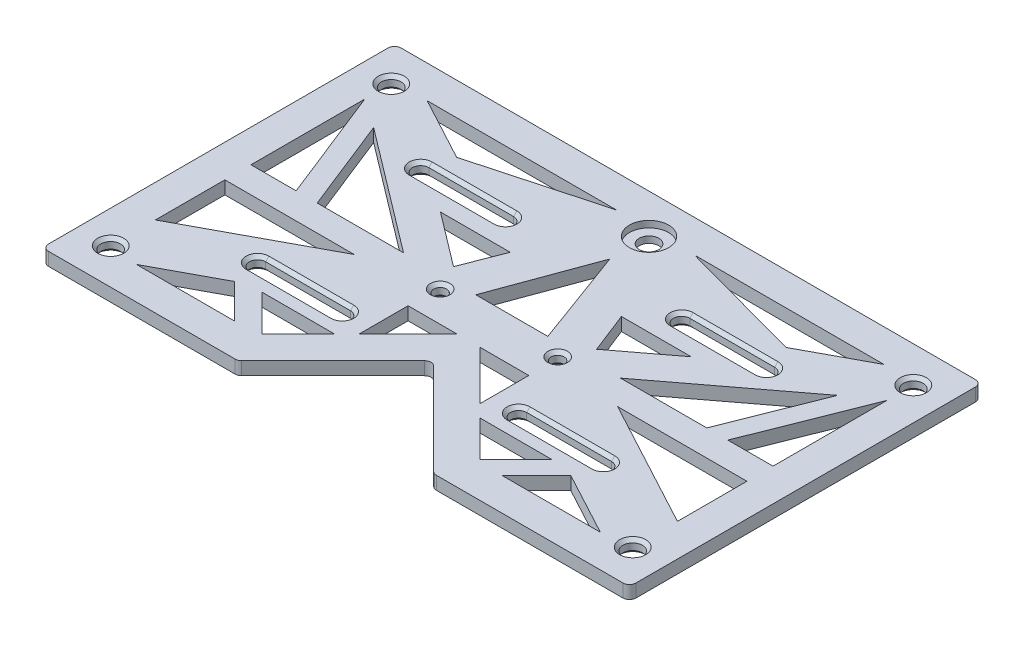
SolidWorks part; units mm, degrees
ref_plane "前视基准面" through (0, 0, 0) normal (0, 0, 1) x (1, 0, 0)
ref_plane "上视基准面" through (0, 0, 0) normal (0, 1, 0) x (1, 0, 0)
ref_plane "右视基准面" through (0, 0, 0) normal (1, 0, 0) x (0, 0, -1)
other "Configuration Table"
sketch "草图1" plane through (0, 0, 0) normal (0, 1, 0) x (1, 0, 0)
  line L0 (0, 26.8995) -> (0, -26.8995) construction
  line L1 (-45, 26.8995) -> (45, 26.8995)
  line L2 (-45, 26.8995) -> (-45, -27.1005)
  line L3 (-45, -27.1005) -> (-15, -27.1005)
  line L4 (45, 26.8995) -> (45, -27.1005)
  line L5 (45, -0.1005) -> (-45, -0.1005) construction
  line L6 (-26.5, 12.3995) -> (-13.5, 12.3995) construction
  line L7 (-26.5, 13.6495) -> (-13.5, 13.6495)
  line L8 (-26.5, 11.1495) -> (-13.5, 11.1495)
  line L9 (-26.5, -12.6005) -> (-13.5, -12.6005) construction
  line L10 (-26.5, -11.3505) -> (-13.5, -11.3505)
  line L11 (-26.5, -13.8505) -> (-13.5, -13.8505)
  line L12 (-40, -21.6005) -> (40, -21.6005) construction
  line L13 (-40, 21.3995) -> (-40, -21.6005) construction
  line L14 (-40, 21.3995) -> (40, 21.3995) construction
  line L15 (40, 21.3995) -> (40, -21.6005) construction
  line L16 (-38.5, 21.3995) -> (-38.5, -21.6005) construction
  line L17 (38.5, -21.6005) -> (38.5, 21.3995) construction
  line L18 (40, 19.8995) -> (-40, 19.8995) construction
  line L19 (-40, -20.1005) -> (40, -20.1005) construction
  line L20 (-20, 12.3995) -> (-20, -12.6005) construction
  line L21 (13.5, 12.3995) -> (26.5, 12.3995) construction
  line L22 (13.5, 13.6495) -> (26.5, 13.6495)
  line L23 (13.5, 11.1495) -> (26.5, 11.1495)
  line L24 (13.5, -12.6005) -> (26.5, -12.6005) construction
  line L25 (13.5, -11.3505) -> (26.5, -11.3505)
  line L26 (13.5, -13.8505) -> (26.5, -13.8505)
  line L27 (20, 12.3995) -> (20, -12.6005) construction
  line L31 (-15, -27.1005) -> (0, -12.1005)
  line L32 (0, -12.1005) -> (15, -27.1005)
  line L34 (0, -12.1005) -> (0, -26.8995) construction
  line L35 (15, -27.1005) -> (45, -27.1005)
  line L36 (-9, -2.1005) -> (9, -2.1005) construction
  arc A0 (-26.5, 13.6495) -> (-26.5, 11.1495) centre (-26.5, 12.3995) ccw
  arc A1 (-13.5, 11.1495) -> (-13.5, 13.6495) centre (-13.5, 12.3995) ccw
  arc A2 (-26.5, -11.3505) -> (-26.5, -13.8505) centre (-26.5, -12.6005) ccw
  arc A3 (-13.5, -13.8505) -> (-13.5, -11.3505) centre (-13.5, -12.6005) ccw
  circle A4 centre (-40, 21.3995) radius 1.5
  circle A5 centre (-40, -21.6005) radius 1.5
  circle A6 centre (40, 21.3995) radius 1.5
  circle A7 centre (40, -21.6005) radius 1.5
  arc A8 (13.5, 13.6495) -> (13.5, 11.1495) centre (13.5, 12.3995) ccw
  arc A9 (26.5, 11.1495) -> (26.5, 13.6495) centre (26.5, 12.3995) ccw
  arc A10 (13.5, -11.3505) -> (13.5, -13.8505) centre (13.5, -12.6005) ccw
  arc A11 (26.5, -13.8505) -> (26.5, -11.3505) centre (26.5, -12.6005) ccw
  circle A12 centre (-9, -2.1005) radius 1
  circle A13 centre (9, -2.1005) radius 1
  circle A14 centre (0, 20.8995) radius 1.5
  point P8 (0, 0)
  point P12 (-20, 12.3995)
  point P17 (-27.75, 12.3995)
  point P18 (-12.25, 12.3995)
  point P21 (-20, -12.6005)
  point P36 (0, -21.6005)
  point P37 (-40, -0.1005)
  point P48 (-20, -0.1005)
  point P51 (20, 12.3995)
  point P60 (20, -12.6005)
  point P65 (0, -2.1005)
  point P69 (20, -0.1005)
  dimension "D6" = 3
  dimension "D14" = 2
  dimension "D17" = 3
  dimension "D19" = 2
  dimension "D1" = 90
  dimension "D2" = 54
  dimension "D3" = 13
  dimension "D4" = 2.5
  dimension "D5" = 15.5
  dimension "D7" = 80
  dimension "D8" = 43
  dimension "D9" = 25
  dimension "D10" = 20
  dimension "D11" = 20
  dimension "D12" = 25
  dimension "D13" = 15
  dimension "D15" = 18
  dimension "D18" = 23
  dimension "D21" = 25
extrude "凸台-拉伸1" add sketch "草图1" along normal blind 2
sketch "草图3" plane through (0, 2, 0) normal (0, 1, 0) x (1, 0, 0)
  circle A2 centre (0, 20.8995) radius 3
  circle A3 centre (0, 20.8995) radius 3
  dimension "D1" = 1.5
extrude "切除-拉伸2" cut sketch "草图3" against normal blind 1 contours A3
sketch "草图2" plane through (0, 2, 0) normal (0, 1, 0) x (1, 0, 0)
  line L8 (-45, 26.8995) -> (-45, -27.1005) construction
  line L16 (45, 26.8995) -> (-45, 26.8995) construction
  line L17 (45, -27.1005) -> (45, 26.8995) construction
  line L18 (-45, -27.1005) -> (-15, -27.1005) construction
  line L19 (-35.5413, -22.1005) -> (-20.5238, -22.1005)
  line L33 (-20.5238, -22.1005) -> (-25.7738, -16.8505)
  line L40 (-25.7738, -16.8505) -> (-35.5413, -22.1005)
  line L47 (-16.6761, -21.7055) -> (-22.2208, -16.1608)
  line L53 (-22.2208, -16.1608) -> (-11.1314, -16.1608)
  line L60 (-11.1314, -16.1608) -> (-16.6761, -21.7055)
  line L61 (-45, -0.1005) -> (45, -0.1005) construction
  line L62 (-40, -14.7479) -> (-20.1909, -4.1005)
  line L63 (-20.1909, -4.1005) -> (-40, -4.1005)
  line L64 (-40, -4.1005) -> (-40, -14.7479)
  line L68 (0, 14.8995) -> (-5.5196, -0.129)
  line L69 (-5.5196, -0.129) -> (5.5196, -0.129)
  line L70 (5.5196, -0.129) -> (0, 14.8995)
  line L71 (0, 14.8995) -> (0, -0.129) construction
  line L72 (-26.5, -13.8505) -> (-13.5, -13.8505) construction
  line L73 (-15, -27.1005) -> (0, -12.1005) construction
  line L74 (-40, -21.6005) -> (40, 21.3995) construction
  line L75 (-40, 21.3995) -> (40, -21.6005) construction
  line L76 (-1.7459, -6.7753) -> (-9.25, -14.2794)
  line L77 (-9.25, -14.2794) -> (-9.25, -6.7753)
  line L78 (-9.25, -6.7753) -> (-1.7459, -6.7753)
  line L79 (-35, 21.8995) -> (-6, 21.8995)
  line L80 (-6, 21.8995) -> (-25.2326, 16.6495)
  line L81 (-25.2326, 16.6495) -> (-35, 21.8995)
  line L85 (-13.5, 13.6495) -> (-26.5, 13.6495) construction
  line L86 (0, 20.8995) -> (-9, -2.1005) construction
  line L87 (-45, -2.1005) -> (-9, -2.1005) construction
  line L88 (9, -2.1005) -> (0, 20.8995) construction
  line L89 (0, 20.8995) -> (0, -12.1005) construction
  line L96 (-29.8493, -0.1005) -> (-35.5436, 14.2406)
  line L97 (-35.5436, 14.2406) -> (-16.6256, -0.1005)
  line L98 (-16.6256, -0.1005) -> (-29.8493, -0.1005)
  line L99 (-40, 21.3995) -> (-26.5, -12.6005) construction
  line L100 (-13.5, -12.6005) -> (-9, -2.1005) construction
  line L101 (26.5, -12.6005) -> (40, 21.3995) construction
  line L102 (13.5, -12.6005) -> (9, -2.1005) construction
  line L103 (-9, -2.1005) -> (9, -2.1005) construction
  line L104 (9, -2.1005) -> (45, -2.1005) construction
  line L105 (-40, 17.3349) -> (-40, -0.1005)
  line L106 (-40, -0.1005) -> (-33.0772, -0.1005)
  line L107 (-33.0772, -0.1005) -> (-40, 17.3349)
  line L108 (-40, 21.3995) -> (-9, -2.1005) construction
  line L109 (9, -2.1005) -> (40, 21.3995) construction
  line L110 (-19.2106, 8.1495) -> (-8.5203, 8.1495)
  line L111 (-8.5203, 8.1495) -> (-10.9659, 1.8995)
  line L112 (-10.9659, 1.8995) -> (-19.2106, 8.1495)
  line L113 (-26.5, 11.1495) -> (-13.5, 11.1495) construction
  line L114 (0, 20.8995) -> (-13.5, 12.3995) construction
  line L115 (-26.5, 12.3995) -> (0, 20.8995) construction
  line L116 (9.25, -14.2794) -> (9.25, -6.7753)
  line L117 (1.7459, -6.7753) -> (9.25, -14.2794)
  line L118 (9.25, -6.7753) -> (1.7459, -6.7753)
  line L119 (22.2208, -16.1608) -> (11.1314, -16.1608)
  line L120 (16.6761, -21.7055) -> (22.2208, -16.1608)
  line L121 (11.1314, -16.1608) -> (16.6761, -21.7055)
  line L122 (20.5238, -22.1005) -> (25.7738, -16.8505)
  line L123 (35.5413, -22.1005) -> (20.5238, -22.1005)
  line L124 (25.7738, -16.8505) -> (35.5413, -22.1005)
  line L125 (20.1909, -4.1005) -> (40, -4.1005)
  line L126 (40, -14.7479) -> (20.1909, -4.1005)
  line L127 (40, -4.1005) -> (40, -14.7479)
  line L128 (8.5203, 8.1495) -> (10.9659, 1.8995)
  line L129 (19.2106, 8.1495) -> (8.5203, 8.1495)
  line L130 (10.9659, 1.8995) -> (19.2106, 8.1495)
  line L131 (35.5436, 14.2406) -> (16.6256, -0.1005)
  line L132 (29.8493, -0.1005) -> (35.5436, 14.2406)
  line L133 (16.6256, -0.1005) -> (29.8493, -0.1005)
  line L134 (40, -0.1005) -> (33.0772, -0.1005)
  line L135 (40, 17.3349) -> (40, -0.1005)
  line L136 (33.0772, -0.1005) -> (40, 17.3349)
  line L137 (6, 21.8995) -> (25.2326, 16.6495)
  line L138 (35, 21.8995) -> (6, 21.8995)
  line L139 (25.2326, 16.6495) -> (35, 21.8995)
  circle A0 centre (0, 20.8995) radius 3 construction
  circle A1 centre (9, -2.1005) radius 1 construction
  arc A3 (-26.5, -11.3505) -> (-26.5, -13.8505) centre (-26.5, -12.6005) ccw construction
  arc A4 (-13.5, -13.8505) -> (-13.5, -11.3505) centre (-13.5, -12.6005) ccw construction
  circle A5 centre (-40, 21.3995) radius 1.5 construction
  circle A6 centre (-9, -2.1005) radius 1 construction
  point P59 (-12.25, -12.6005)
  dimension "D4" = 4
  dimension "D12" = 4.5
  dimension "D1" = 6
  dimension "D3" = 5
  dimension "D5" = 6
  dimension "D6" = 2.3104
  dimension "D7" = 5
  dimension "D8" = 3
  dimension "D9" = 5
  dimension "D10" = 3
  dimension "D11" = 5
  dimension "D13" = 3
  dimension "D14" = 2
  dimension "D15" = 3
  dimension "D16" = 5
  dimension "D17" = 1.5
  dimension "D18" = 5
  dimension "D19" = 3
  dimension "D20" = 2
  dimension "D21" = 5
  dimension "D22" = 4
  dimension "D23" = 2
  dimension "D24" = 1.5
  dimension "D25" = 1.5
  dimension "D26" = 2
  dimension "D27" = 3
extrude "切除-拉伸3" cut sketch "草图2" against normal blind 2
fillet "圆角3" radius 1 7 edges at (45, 1, -26.8995) (-45, 1, -26.8995) (-45, 1, 27.1005) (45, 1, 27.1005) (15, 1, 27.1005) (-15, 1, 27.1005) (0, 1, 12.1005)
chamfer "倒角2" distance 0.5 angle 45 44 edges at (-20, 0, -13.6495) (-27.75, 0, -12.3995) (-20, 0, -11.1495) (-12.25, 0, -12.3995) (20, 0, -13.6495) (12.25, 0, -12.3995) (20, 0, -11.1495) (27.75, 0, -12.3995) (20, 0, 11.3505) (12.25, 0, 12.6005) (20, 0, 13.8505) (27.75, 0, 12.6005) (-20, 0, 11.3505) (-27.75, 0, 12.6005) (-20, 0, 13.8505) (-12.25, 0, 12.6005) (-27.75, 2, 12.6005) (-20, 2, 13.8505) (-12.25, 2, 12.6005) (-20, 2, 11.3505) (12.25, 2, 12.6005) (20, 2, 13.8505) (27.75, 2, 12.6005) (20, 2, 11.3505) (12.25, 2, -12.3995) (20, 2, -11.1495) (27.75, 2, -12.3995) (20, 2, -13.6495) (-20, 2, -11.1495) (-27.75, 2, -12.3995) (-20, 2, -13.6495) (-12.25, 2, -12.3995) (40, 2, 23.1005) (40, 0, 23.1005) (-40, 2, 23.1005) (-40, 0, 23.1005) (-9, 2, 3.1005) (-9, 0, 3.1005) (9, 2, 3.1005) (9, 0, 3.1005) (40, 2, -19.8995) (40, 0, -19.8995) (-40, 2, -19.8995) (-40, 0, -19.8995)
